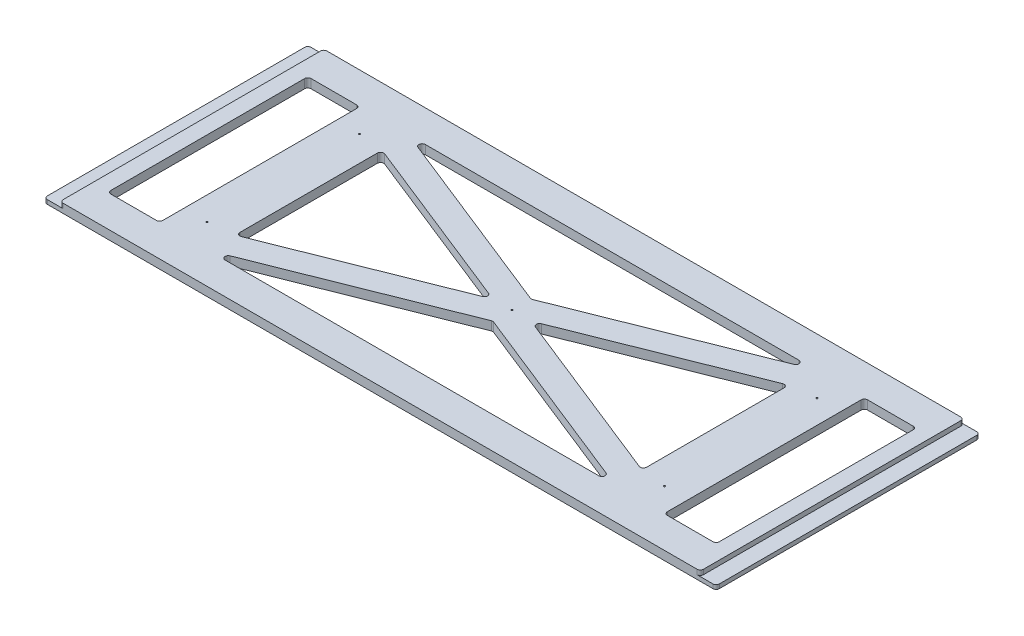
SolidWorks part; units mm, degrees
ref_plane "Front Plane" through (0, 0, 0) normal (0, 0, 1) x (1, 0, 0)
ref_plane "Top Plane" through (0, 0, 0) normal (0, 1, 0) x (1, 0, 0)
ref_plane "Right Plane" through (0, 0, 0) normal (1, 0, 0) x (0, 0, -1)
sketch "Sketch1" plane through (0, 0, 0) normal (0, 1, 0) x (1, 0, 0)
  line L1 (-671.5125, 263.525) -> (671.5125, 263.525)
  line L2 (-671.5125, 263.525) -> (-671.5125, -263.525)
  line L3 (-671.5125, -263.525) -> (671.5125, -263.525)
  line L4 (671.5125, 263.525) -> (671.5125, -263.525)
  line L5 (-671.5125, 263.525) -> (671.5125, -263.525) construction
  line L6 (-671.5125, -263.525) -> (671.5125, 263.525) construction
  point P0 (0, 0)
  dimension "D1" = 527.05
  dimension "D2" = 1343.025
extrude "Boss-Extrude1" add sketch "Sketch1" along normal blind 17.78
fillet "Fillet1" radius 6.35 4 edges at (-671.5125, 8.89, 263.525) (-671.5125, 8.89, -263.525) (671.5125, 8.89, -263.525) (671.5125, 8.89, 263.525)
hole_wizard "1/8 (0.125) Diameter Hole1" positions "Sketch3" profile "Sketch4" hole size "1/8" standard "ANSI Inch" end condition through all
sketch "Sketch3" plane through (0, 17.78, 0) normal (0, 1, 0) x (1, 0, 0)
  line L1 (-457.2, -152.4) -> (457.2, -152.4) construction
  line L2 (-457.2, -152.4) -> (-457.2, 152.4) construction
  line L3 (-457.2, 152.4) -> (457.2, 152.4) construction
  line L4 (457.2, -152.4) -> (457.2, 152.4) construction
  line L5 (-457.2, -152.4) -> (457.2, 152.4) construction
  line L6 (-457.2, 152.4) -> (457.2, -152.4) construction
  point P0 (0, 0)
  point P1 (457.2, 152.4)
  point P32 (-457.2, -152.4)
  point P33 (-457.2, 152.4)
  point P34 (457.2, -152.4)
  dimension "D1" = 914.4
  dimension "D2" = 304.8
sketch "Sketch4" plane through (0, 17.78, 0) normal (1, 0, 0) x (0, 0, 1)
  line L0 (0, 0) -> (0, 17.78)
  line L1 (0, 17.78) -> (1.5875, 17.78)
  line L2 (1.5875, 17.78) -> (1.5875, 0)
  line L5 (1.5875, 0) -> (0, 0)
  line L11 (0, -6.35) -> (0, 107.95) construction
  dimension "Thru Hole Dia." = 3.175
  dimension "Thru Hole Depth" = 17.78
sketch "Sketch2" plane through (0, 17.78, 0) normal (0, 1, 0) x (1, 0, 0)
  line L1 (-635, -330.2) -> (635, -330.2)
  line L2 (-635, -330.2) -> (-635, 330.2)
  line L3 (-635, 330.2) -> (635, 330.2)
  line L4 (635, -330.2) -> (635, 330.2)
  line L5 (-635, -330.2) -> (635, 330.2) construction
  line L6 (-635, 330.2) -> (635, -330.2) construction
  point P0 (0, 0)
  dimension "D1" = 660.4
  dimension "D2" = 1270
extrude "Boss-Extrude2" [suppressed] add sketch "Sketch2" along normal blind 9.525
sketch "Sketch5" plane through (0, 17.78, 0) normal (0, 1, 0) x (1, 0, 0)
  line L0 (-406.4, 200.025) -> (406.4, 200.025)
  line L1 (665.1625, 263.525) -> (-665.1625, 263.525) construction
  line L2 (0, 38.1) -> (-406.4, 200.025)
  line L3 (406.4, 200.025) -> (0, 38.1)
  line L4 (0, 263.525) -> (0, -263.525) construction
  line L5 (-665.1625, -263.525) -> (665.1625, -263.525) construction
  line L6 (-671.5125, 0) -> (671.5125, 0) construction
  line L7 (-671.5125, 257.175) -> (-671.5125, -257.175) construction
  line L8 (671.5125, -257.175) -> (671.5125, 257.175) construction
  line L9 (0, -38.1) -> (-406.4, -200.025)
  line L10 (-406.4, -200.025) -> (406.4, -200.025)
  line L11 (406.4, -200.025) -> (0, -38.1)
  line L12 (406.4, 146.7445) -> (406.4, -146.7445)
  line L13 (406.4, -146.7445) -> (38.1, 0)
  line L14 (406.4, 146.7445) -> (38.1, 0)
  line L15 (-406.4, 146.7445) -> (-38.1, 0)
  line L16 (-406.4, 146.7445) -> (-406.4, -146.7445)
  line L17 (-406.4, -146.7445) -> (-38.1, 0)
  line L18 (608.0125, -200.025) -> (504.1452, -200.025)
  line L19 (-608.0125, -200.025) -> (-504.1452, -200.025)
  line L20 (-608.0125, -200.025) -> (-608.0125, 200.025)
  line L21 (-608.0125, 200.025) -> (-504.1452, 200.025)
  line L22 (-504.1452, -200.025) -> (-504.1452, 200.025)
  line L23 (-608.0125, -200.025) -> (-504.1452, 200.025) construction
  line L24 (-608.0125, 200.025) -> (-504.1452, -200.025) construction
  line L25 (608.0125, -200.025) -> (608.0125, 200.025)
  line L26 (608.0125, 200.025) -> (504.1452, 200.025)
  line L27 (504.1452, -200.025) -> (504.1452, 200.025)
  circle A0 centre (0, 0) radius 38.1 construction
  point P3 (0, 200.025)
  point P30 (-556.0789, 0)
  dimension "D2" = 76.2
  dimension "D4" = 115.4336
  dimension "D1" = 63.5
  dimension "D3" = 812.8
  dimension "D5" = 63.5
extrude "Cut-Extrude1" cut sketch "Sketch5" against normal through all
sketch "Sketch6" plane through (0, 17.78, 0) normal (0, 1, 0) x (1, 0, 0)
  line L0 (-665.1625, -263.525) -> (665.1625, -263.525) construction
  line L3 (639.7625, -263.525) -> (665.1625, -263.525)
  line L4 (639.7625, -263.525) -> (639.7625, 263.525)
  line L5 (639.7625, 263.525) -> (665.1625, 263.525)
  line L6 (671.5125, -257.175) -> (671.5125, 257.175)
  line L7 (671.5125, -257.175) -> (671.5125, 257.175) construction
  line L8 (-639.7625, -263.525) -> (-665.1625, -263.525)
  line L9 (-639.7625, -263.525) -> (-639.7625, 263.525)
  line L10 (-639.7625, 263.525) -> (-665.1625, 263.525)
  line L11 (-671.5125, -257.175) -> (-671.5125, 257.175)
  arc A0 (671.5125, 257.175) -> (665.1625, 263.525) centre (665.1625, 257.175) ccw construction
  arc A1 (665.1625, -263.525) -> (671.5125, -257.175) centre (665.1625, -257.175) ccw construction
  arc A2 (671.5125, 257.175) -> (665.1625, 263.525) centre (665.1625, 257.175) ccw
  arc A3 (665.1625, -263.525) -> (671.5125, -257.175) centre (665.1625, -257.175) ccw
  arc A4 (-665.1625, 263.525) -> (-671.5125, 257.175) centre (-665.1625, 257.175) ccw construction
  arc A5 (-671.5125, -257.175) -> (-665.1625, -263.525) centre (-665.1625, -257.175) ccw construction
  arc A6 (-665.1625, 263.525) -> (-671.5125, 257.175) centre (-665.1625, 257.175) ccw
  arc A7 (-671.5125, -257.175) -> (-665.1625, -263.525) centre (-665.1625, -257.175) ccw
  dimension "D1" = 31.75
  dimension "D2" = 31.75
extrude "Cut-Extrude2" cut sketch "Sketch6" against normal blind 9.525
fillet "Fillet2" radius 6.35 24 edges at (504.1452, 8.89, -200.025) (504.1452, 8.89, 200.025) (608.0125, 8.89, 200.025) (406.4, 8.89, 146.7445) (406.4, 8.89, 200.025) (608.0125, 8.89, -200.025) (406.4, 8.89, -146.7445) (406.4, 8.89, -200.025) (38.1, 8.89, 0) (0, 8.89, 38.1) (0, 8.89, -38.1) (-38.1, 8.89, 0) (-406.4, 8.89, 200.025) (-406.4, 8.89, -200.025) (-406.4, 8.89, -146.7445) (-406.4, 8.89, 146.7445) (-608.0125, 8.89, 200.025) (-504.1452, 8.89, 200.025) (-504.1452, 8.89, -200.025) (-608.0125, 8.89, -200.025) (639.7625, 13.0175, 263.525) (639.7625, 13.0175, -263.525) (-639.7625, 13.0175, 263.525) (-639.7625, 13.0175, -263.525)
